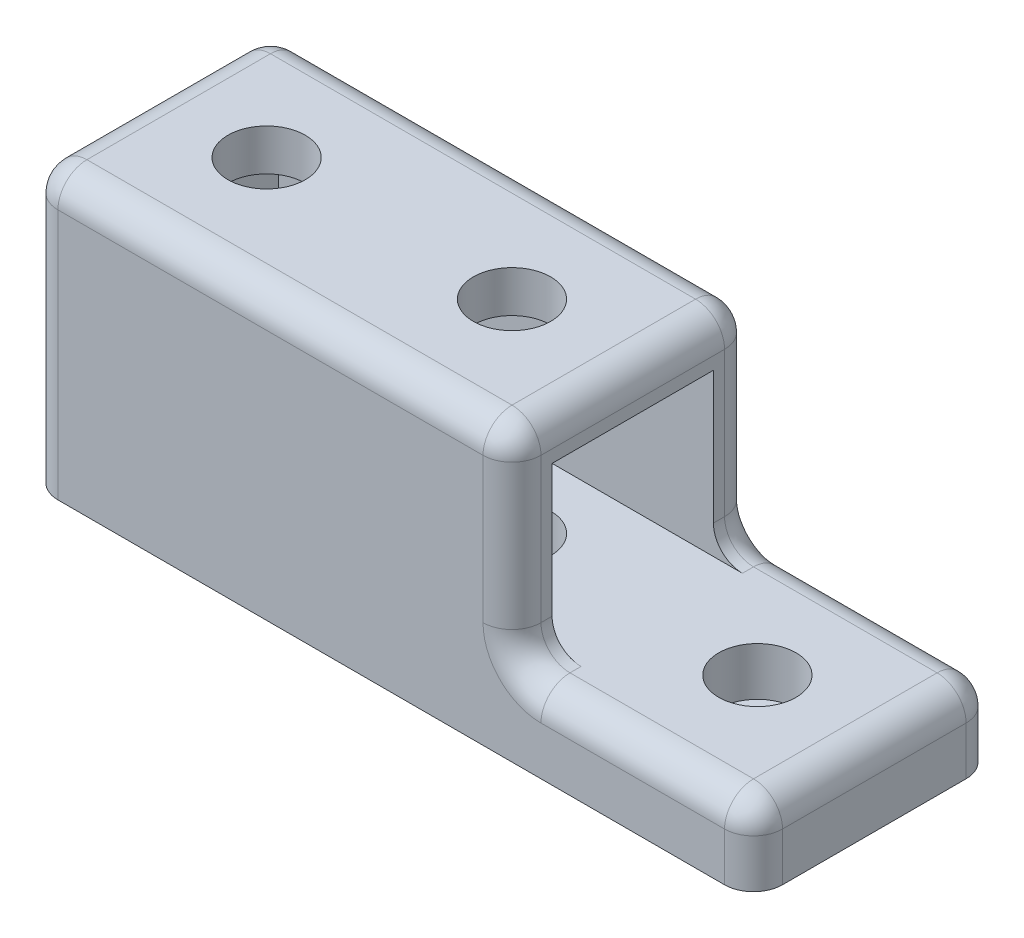
SolidWorks part; units mm, degrees
material "ABS"
ref_plane "Front Plane" through (0, 0, 0) normal (0, 0, 1) x (1, 0, 0)
ref_plane "Top Plane" through (0, 0, 0) normal (0, 1, 0) x (1, 0, 0)
ref_plane "Right Plane" through (0, 0, 0) normal (1, 0, 0) x (0, 0, -1)
sketch "Sketch1" plane through (0, 0, 0) normal (0, 1, 0) x (1, 0, 0)
  line L1 (-37.5, -12.5) -> (37.5, -12.5)
  line L2 (-37.5, -12.5) -> (-37.5, 12.5)
  line L3 (-37.5, 12.5) -> (37.5, 12.5)
  line L4 (37.5, -12.5) -> (37.5, 12.5)
  line L5 (-37.5, -12.5) -> (37.5, 12.5) construction
  line L6 (-37.5, 12.5) -> (37.5, -12.5) construction
  point P0 (0, 0)
  dimension "D1" = 25
  dimension "D2" = 75
extrude "Boss-Extrude1" add sketch "Sketch1" along normal blind 8
sketch "Sketch5" plane through (-37.5, 0, 0) normal (-1, 0, 0) x (0, 0, 1)
  line L1 (-12.5, 8) -> (12.5, 8)
  line L2 (-12.5, 8) -> (-12.5, 29)
  line L3 (-12.5, 29) -> (12.5, 29)
  line L4 (12.5, 8) -> (12.5, 29)
  dimension "D1" = 25
  dimension "D2" = 21
extrude "Boss-Extrude2" add sketch "Sketch5" against normal blind 50
sketch "Sketch7" plane through (12.5, 0, 0) normal (1, 0, 0) x (0, 0, -1)
  line L0 (-8.35, 8) -> (-8.35, 24.7)
  line L5 (-8.35, 24.7) -> (8.35, 24.7)
  line L6 (-8.35, 8) -> (8.35, 8)
  line L7 (8.35, 24.7) -> (8.35, 8)
  line L8 (12.5, 8) -> (-12.5, 8) construction
  point P5 (0, 8)
  dimension "D1" = 16.7
  dimension "D2" = 16.7
extrude "Cut-Extrude3" cut sketch "Sketch7" against normal blind 45
sketch "Sketch4" plane through (0, 0, 0) normal (0, 1, 0) x (1, 0, 0)
  line L0 (-25.4, 0) -> (25.4, 0) construction
  circle A0 centre (0, 0) radius 2.3813
  circle A1 centre (25.4, 0) radius 2.3813
  circle A2 centre (-25.4, 0) radius 2.3813
  point P5 (0, 0)
extrude "Cut-Extrude2" cut sketch "Sketch4" along normal through all
sketch "Sketch3" plane through (0, 8, 0) normal (0, 1, 0) x (1, 0, 0)
  line L0 (-25.4, 0) -> (25.4, 0) construction
  circle A0 centre (0, 0) radius 4
  circle A1 centre (25.4, 0) radius 4
  circle A2 centre (-25.4, 0) radius 4
  point P4 (0, 0)
extrude "Cut-Extrude1" cut sketch "Sketch3" against normal blind 5 and the other way through all
fillet "Fillet1" radius 3 15 edges at (-37.5, 14.5, -12.5) (-37.5, 14.5, 12.5) (-37.5, 29, 0) (12.5, 29, 0) (-12.5, 29, 12.5) (-12.5, 29, -12.5) (25, 8, -12.5) (12.5, 18.5, -12.5) (37.5, 4, -12.5) (37.5, 4, 12.5) (37.5, 8, 0) (25, 8, 12.5) (12.5, 8, 10.425) (12.5, 18.5, 12.5) (12.5, 8, -10.425)
sketch "Sketch8" plane through (-32.5, 0, 0) normal (1, 0, 0) x (0, 0, -1)
  circle A0 centre (0, 16.35) radius 3.175
extrude "Cut-Extrude4" cut sketch "Sketch8" against normal through all
